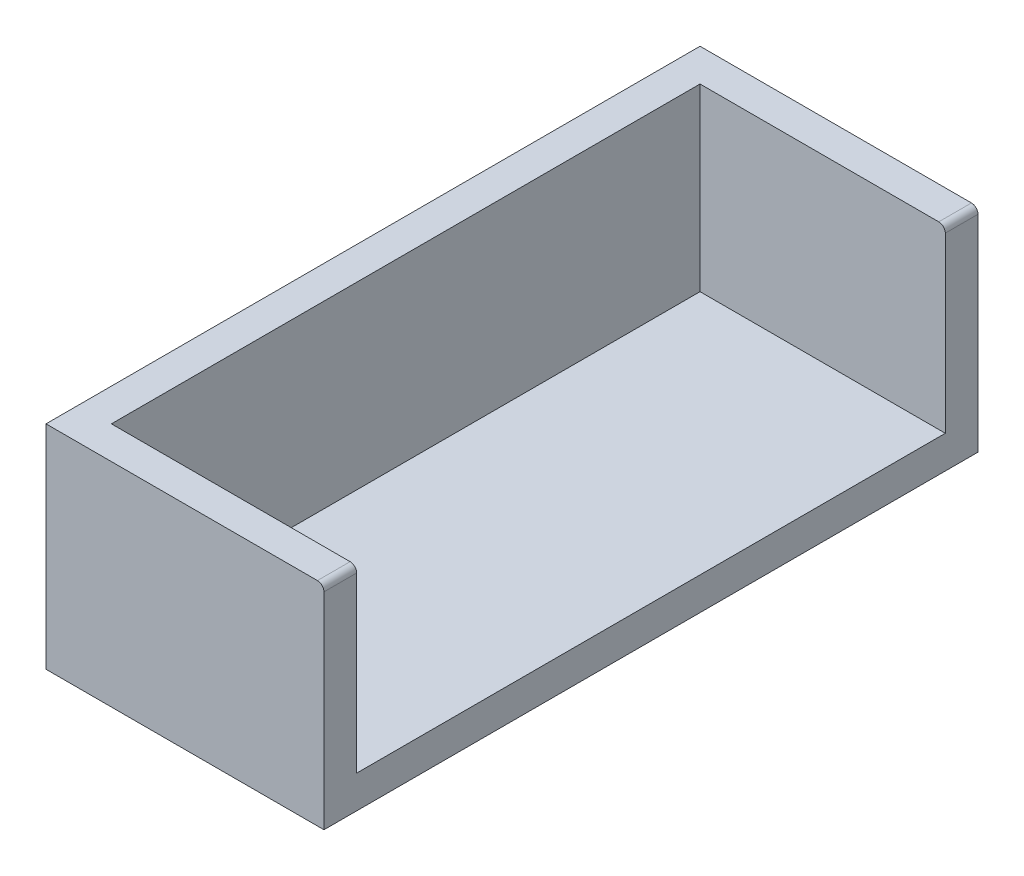
SolidWorks part; units mm, degrees
ref_plane "Front Plane" through (0, 0, 0) normal (0, 0, 1) x (1, 0, 0)
ref_plane "Top Plane" through (0, 0, 0) normal (0, 1, 0) x (1, 0, 0)
ref_plane "Right Plane" through (0, 0, 0) normal (1, 0, 0) x (0, 0, -1)
sketch "Sketch1" plane through (0, 0, 0) normal (0, 0, 1) x (1, 0, 0)
  line L1 (0, 0) -> (850, 0)
  line L2 (0, 0) -> (0, 650)
  line L3 (0, 650) -> (830, 650)
  line L4 (850, 0) -> (850, 630)
  arc A0 (830, 650) -> (850, 630) centre (830, 630) cw
  point P7 (850, 650)
  dimension "D3" = 20
  dimension "D1" = 650
  dimension "D2" = 850
extrude "Boss-Extrude1" add sketch "Sketch1" along normal blind 2000
sketch "Sketch2" plane through (0, 650, 0) normal (0, 1, 0) x (1, 0, 0)
  line L0 (0, -2000) -> (0, 0) construction
  line L1 (100, -100) -> (1115.3984, -100)
  line L2 (100, -100) -> (100, -1900)
  line L3 (100, -1900) -> (1115.3984, -1900)
  line L4 (1115.3984, -100) -> (1115.3984, -1900)
  line L5 (830, -2000) -> (0, -2000) construction
  line L6 (830, 0) -> (0, 0) construction
  dimension "D1" = 100
  dimension "D2" = 100
  dimension "D3" = 100
extrude "Cut-Extrude1" cut sketch "Sketch2" against normal blind 550
sketch "Sketch3" plane through (0, 0, 0) normal (0, -1, 0) x (1, 0, 0)
  line L0 (425, 2000) -> (425, 0) construction
  line L1 (0, 2000) -> (150, 2000) construction
  line L2 (0, 2000) -> (0, 1850) construction
  line L3 (0, 1850) -> (150, 1850) construction
  line L4 (150, 2000) -> (150, 1850) construction
  line L5 (0, 2000) -> (850, 2000) construction
  line L6 (0, 0) -> (850, 0) construction
  line L7 (0, 1000) -> (850, 1000) construction
  line L8 (0, 2000) -> (0, 0) construction
  line L9 (850, 2000) -> (850, 0) construction
  circle A0 centre (150, 1850) radius 40
  circle A1 centre (700, 1850) radius 40
  circle A2 centre (700, 150) radius 40
  circle A3 centre (150, 150) radius 40
  dimension "D3" = 80
  dimension "D1" = 150
  dimension "D2" = 150
extrude "Boss-Extrude2" add sketch "Sketch3" along normal blind 20
